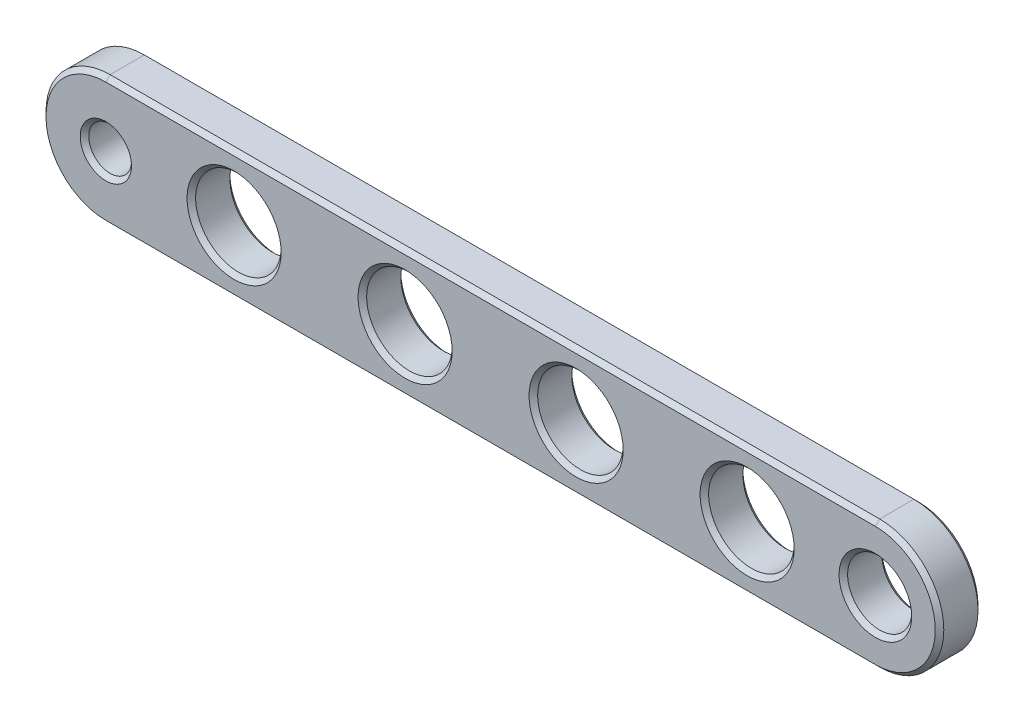
SolidWorks part; units mm, degrees
ref_plane "Front Plane" through (0, 0, 0) normal (0, 0, 1) x (1, 0, 0)
ref_plane "Top Plane" through (0, 0, 0) normal (0, 1, 0) x (1, 0, 0)
ref_plane "Right Plane" through (0, 0, 0) normal (1, 0, 0) x (0, 0, -1)
sketch "Sketch1" plane through (0, 0, 0) normal (0, 0, 1) x (1, 0, 0)
  line L0 (-18, 0) -> (18, 0) construction
  line L1 (-18, 3) -> (18, 3)
  line L2 (-18, -3) -> (18, -3)
  arc A0 (-18, 3) -> (-18, -3) centre (-18, 0) ccw
  arc A1 (18, -3) -> (18, 3) centre (18, 0) ccw
  circle A2 centre (-18, 0) radius 1
  circle A3 centre (-12, 0) radius 2
  circle A4 centre (-4, 0) radius 2
  circle A5 centre (18, 0) radius 1.5
  circle A6 centre (12, 0) radius 2
  circle A7 centre (4, 0) radius 2
  point P2 (0, 0)
  dimension "D2" = 3
  dimension "D3" = 2
  dimension "D4" = 3
  dimension "D5" = 4
  dimension "D1" = 36
  dimension "D6" = 6
  dimension "D7" = 8
  dimension "D8" = 6
  dimension "D9" = 8
extrude "Boss-Extrude1" add sketch "Sketch1" along normal blind 2
chamfer "Chamfer1" distance 0.2 angle 45 20 edges at (6, 0, 0) (14, 0, 0) (19.5, 0, 0) (-2, 0, 0) (-10, 0, 0) (-17, 0, 0) (0, -3, 0) (21, 0, 0) (0, 3, 0) (-21, 0, 0) (6, 0, 2) (19.5, 0, 2) (-10, 0, 2) (0, 3, 2) (21, 0, 2) (0, -3, 2) (-21, 0, 2) (-17, 0, 2) (-2, 0, 2) (14, 0, 2)
